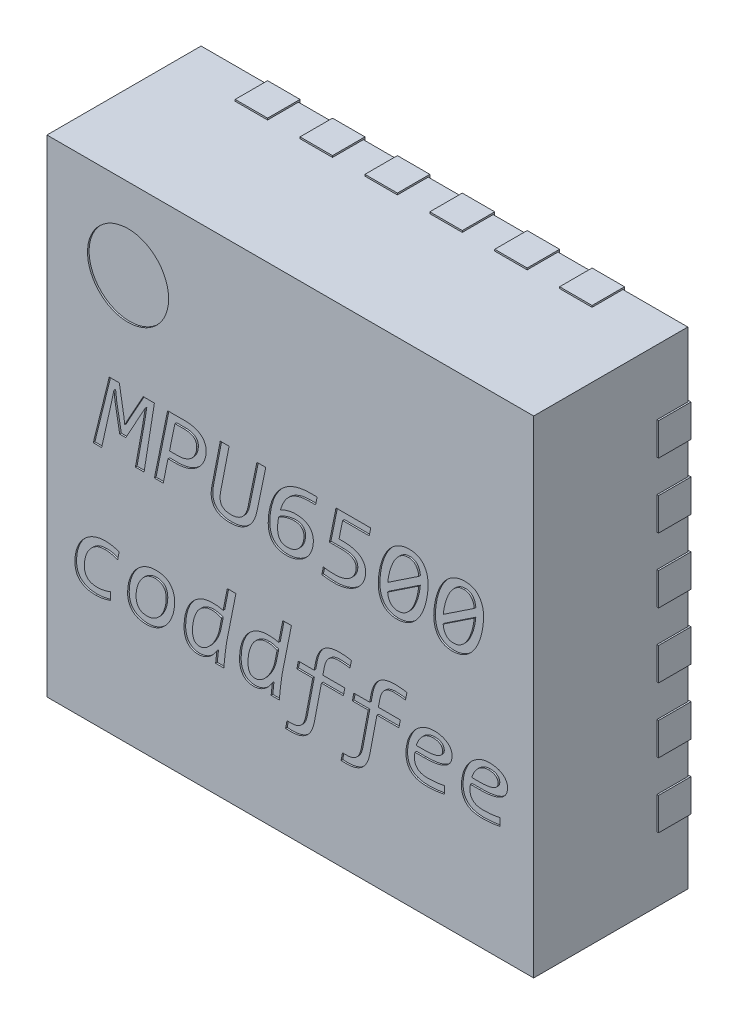
SolidWorks part; units mm, degrees
material "1023 碳钢板 (SS)"
ref_plane "前视基准面" through (0, 0, 0) normal (0, 0, 1) x (1, 0, 0)
ref_plane "上视基准面" through (0, 0, 0) normal (0, 1, 0) x (1, 0, 0)
ref_plane "右视基准面" through (0, 0, 0) normal (1, 0, 0) x (0, 0, -1)
ref_plane "芯片基底面" through (0, 0, 0.01) normal (0, 0, 1) x (1, 0, 0)
sketch "草图1" plane through (0, 0, 0.01) normal (0, 0, 1) x (1, 0, 0)
  line L1 (-1.5, 1.5) -> (1.5, 1.5)
  line L2 (-1.5, 1.5) -> (-1.5, -1.5)
  line L3 (-1.5, -1.5) -> (1.5, -1.5)
  line L4 (1.5, 1.5) -> (1.5, -1.5)
  line L5 (-1.5, 1.5) -> (1.5, -1.5) construction
  line L6 (-1.5, -1.5) -> (1.5, 1.5) construction
  point P0 (0, 0)
extrude "凸台-拉伸1" add sketch "草图1" along normal blind 0.95
sketch "草图2" plane through (0, 0, 0) normal (0, 0, 1) x (1, 0, 0)
  line L0 (0.5, 1.5) -> (0.5, 1.51)
  line L2 (0.9, 1.5) -> (0.9, 1.51)
  line L8 (1.1, 1.51) -> (1.1, 1.2)
  line L9 (1.1, 1.2) -> (0.9, 1.2)
  line L10 (0.9, 1.5) -> (0.9, 1.2)
  line L11 (0.7, 1.51) -> (0.7, 1.2)
  line L12 (0.7, 1.2) -> (0.5, 1.2)
  line L13 (0.9, 1.51) -> (1.1, 1.51)
  line L14 (0.5, 1.5) -> (0.5, 1.2)
  line L15 (0.5, 1.51) -> (0.7, 1.51)
  line L16 (0.1, 1.5) -> (0.1, 1.51)
  line L17 (0.3, 1.51) -> (0.3, 1.2)
  line L18 (0.3, 1.2) -> (0.1, 1.2)
  line L19 (0.1, 1.5) -> (0.1, 1.2)
  line L20 (0.1, 1.51) -> (0.3, 1.51)
  line L21 (-0.3, 1.5) -> (-0.3, 1.51)
  line L22 (-0.1, 1.51) -> (-0.1, 1.2)
  line L23 (-0.1, 1.2) -> (-0.3, 1.2)
  line L24 (-0.3, 1.5) -> (-0.3, 1.2)
  line L25 (-0.3, 1.51) -> (-0.1, 1.51)
  line L26 (-0.7, 1.5) -> (-0.7, 1.51)
  line L27 (-0.5, 1.51) -> (-0.5, 1.2)
  line L28 (-0.5, 1.2) -> (-0.7, 1.2)
  line L29 (-0.7, 1.5) -> (-0.7, 1.2)
  line L30 (-0.7, 1.51) -> (-0.5, 1.51)
  line L31 (-1.1, 1.5) -> (-1.1, 1.51)
  line L32 (-0.9, 1.51) -> (-0.9, 1.2)
  line L33 (-0.9, 1.2) -> (-1.1, 1.2)
  line L34 (-1.1, 1.5) -> (-1.1, 1.2)
  line L35 (-1.1, 1.51) -> (-0.9, 1.51)
  line L36 (1.5, -0.5) -> (1.51, -0.5)
  line L37 (1.5, -0.9) -> (1.51, -0.9)
  line L38 (1.51, -1.1) -> (1.2, -1.1)
  line L39 (1.2, -1.1) -> (1.2, -0.9)
  line L40 (1.5, -0.9) -> (1.2, -0.9)
  line L41 (1.51, -0.7) -> (1.2, -0.7)
  line L42 (1.2, -0.7) -> (1.2, -0.5)
  line L43 (1.51, -0.9) -> (1.51, -1.1)
  line L44 (1.5, -0.5) -> (1.2, -0.5)
  line L45 (1.51, -0.5) -> (1.51, -0.7)
  line L46 (1.5, -0.1) -> (1.51, -0.1)
  line L47 (1.51, -0.3) -> (1.2, -0.3)
  line L48 (1.2, -0.3) -> (1.2, -0.1)
  line L49 (1.5, -0.1) -> (1.2, -0.1)
  line L50 (1.51, -0.1) -> (1.51, -0.3)
  line L51 (1.5, 0.3) -> (1.51, 0.3)
  line L52 (1.51, 0.1) -> (1.2, 0.1)
  line L53 (1.2, 0.1) -> (1.2, 0.3)
  line L54 (1.5, 0.3) -> (1.2, 0.3)
  line L55 (1.51, 0.3) -> (1.51, 0.1)
  line L56 (1.5, 0.7) -> (1.51, 0.7)
  line L57 (1.51, 0.5) -> (1.2, 0.5)
  line L58 (1.2, 0.5) -> (1.2, 0.7)
  line L59 (1.5, 0.7) -> (1.2, 0.7)
  line L60 (1.51, 0.7) -> (1.51, 0.5)
  line L61 (1.5, 1.1) -> (1.51, 1.1)
  line L62 (1.51, 0.9) -> (1.2, 0.9)
  line L63 (1.2, 0.9) -> (1.2, 1.1)
  line L64 (1.5, 1.1) -> (1.2, 1.1)
  line L65 (1.51, 1.1) -> (1.51, 0.9)
  line L66 (-0.5, -1.5) -> (-0.5, -1.51)
  line L67 (-0.9, -1.5) -> (-0.9, -1.51)
  line L68 (-1.1, -1.51) -> (-1.1, -1.2)
  line L69 (-1.1, -1.2) -> (-0.9, -1.2)
  line L70 (-0.9, -1.5) -> (-0.9, -1.2)
  line L71 (-0.7, -1.51) -> (-0.7, -1.2)
  line L72 (-0.7, -1.2) -> (-0.5, -1.2)
  line L73 (-0.9, -1.51) -> (-1.1, -1.51)
  line L74 (-0.5, -1.5) -> (-0.5, -1.2)
  line L75 (-0.5, -1.51) -> (-0.7, -1.51)
  line L76 (-0.1, -1.5) -> (-0.1, -1.51)
  line L77 (-0.3, -1.51) -> (-0.3, -1.2)
  line L78 (-0.3, -1.2) -> (-0.1, -1.2)
  line L79 (-0.1, -1.5) -> (-0.1, -1.2)
  line L80 (-0.1, -1.51) -> (-0.3, -1.51)
  line L81 (0.3, -1.5) -> (0.3, -1.51)
  line L82 (0.1, -1.51) -> (0.1, -1.2)
  line L83 (0.1, -1.2) -> (0.3, -1.2)
  line L84 (0.3, -1.5) -> (0.3, -1.2)
  line L85 (0.3, -1.51) -> (0.1, -1.51)
  line L86 (0.7, -1.5) -> (0.7, -1.51)
  line L87 (0.5, -1.51) -> (0.5, -1.2)
  line L88 (0.5, -1.2) -> (0.7, -1.2)
  line L89 (0.7, -1.5) -> (0.7, -1.2)
  line L90 (0.7, -1.51) -> (0.5, -1.51)
  line L91 (1.1, -1.5) -> (1.1, -1.51)
  line L92 (0.9, -1.51) -> (0.9, -1.2)
  line L93 (0.9, -1.2) -> (1.1, -1.2)
  line L94 (1.1, -1.5) -> (1.1, -1.2)
  line L95 (1.1, -1.51) -> (0.9, -1.51)
  line L96 (-1.5, 0.5) -> (-1.51, 0.5)
  line L97 (-1.5, 0.9) -> (-1.51, 0.9)
  line L98 (-1.51, 1.1) -> (-1.2, 1.1)
  line L99 (-1.2, 1.1) -> (-1.2, 0.9)
  line L100 (-1.5, 0.9) -> (-1.2, 0.9)
  line L101 (-1.51, 0.7) -> (-1.2, 0.7)
  line L102 (-1.2, 0.7) -> (-1.2, 0.5)
  line L103 (-1.51, 0.9) -> (-1.51, 1.1)
  line L104 (-1.5, 0.5) -> (-1.2, 0.5)
  line L105 (-1.51, 0.5) -> (-1.51, 0.7)
  line L106 (-1.5, 0.1) -> (-1.51, 0.1)
  line L107 (-1.51, 0.3) -> (-1.2, 0.3)
  line L108 (-1.2, 0.3) -> (-1.2, 0.1)
  line L109 (-1.5, 0.1) -> (-1.2, 0.1)
  line L110 (-1.51, 0.1) -> (-1.51, 0.3)
  line L111 (-1.5, -0.3) -> (-1.51, -0.3)
  line L112 (-1.51, -0.1) -> (-1.2, -0.1)
  line L113 (-1.2, -0.1) -> (-1.2, -0.3)
  line L114 (-1.5, -0.3) -> (-1.2, -0.3)
  line L115 (-1.51, -0.3) -> (-1.51, -0.1)
  line L116 (-1.5, -0.7) -> (-1.51, -0.7)
  line L117 (-1.51, -0.5) -> (-1.2, -0.5)
  line L118 (-1.2, -0.5) -> (-1.2, -0.7)
  line L119 (-1.5, -0.7) -> (-1.2, -0.7)
  line L120 (-1.51, -0.7) -> (-1.51, -0.5)
  line L121 (-1.5, -1.1) -> (-1.51, -1.1)
  line L122 (-1.51, -0.9) -> (-1.2, -0.9)
  line L123 (-1.2, -0.9) -> (-1.2, -1.1)
  line L124 (-1.5, -1.1) -> (-1.2, -1.1)
  line L125 (-1.51, -1.1) -> (-1.51, -0.9)
  point P123 (0, 0)
  dimension "D1" = 6
  dimension "D2" = 4
extrude "凸台-拉伸2" add sketch "草图2" along normal blind 0.2
sketch "草图3" plane through (0, 0, 0) normal (0, 0, 1) x (1, 0, 0)
  line L0 (-0.6, 0.77) -> (-0.85, 0.52)
  line L1 (0.75, 0.77) -> (-0.6, 0.77)
  line L2 (0.85, 0.67) -> (0.85, -0.67)
  line L3 (0.75, -0.77) -> (-0.75, -0.77)
  line L4 (-0.85, 0.52) -> (-0.85, -0.67)
  arc A0 (-0.85, -0.67) -> (-0.75, -0.77) centre (-0.75, -0.67) ccw
  arc A1 (0.75, -0.77) -> (0.85, -0.67) centre (0.75, -0.67) ccw
  arc A2 (0.85, 0.67) -> (0.75, 0.77) centre (0.75, 0.67) ccw
  point P0 (0, 0)
  point P4 (-0.85, 0.77)
  dimension "D1" = 0.1
extrude "凸台-拉伸3" add sketch "草图3" along normal blind 0.01
sketch "草图4" plane through (0, 0, 0.96) normal (0, 0, 1) x (1, 0, 0)
  line L0 (-1.5, 0) -> (1.5, 0) construction
  line L2 (-1.5, 1.5) -> (-1.5, -1.5) construction
  line L3 (1.5, -1.5) -> (1.5, 1.5) construction
  line L5 (-1.5, -0.8) -> (1.5, -0.8) construction
  circle A0 centre (-1, 1) radius 0.25
  text T0 "<i>MPU6500</i>" font "Consolas" height 0.4
  text T1 "<i>coddffee</i>" font "Consolas" height 0.4
extrude "切除-拉伸1" cut sketch "草图4" against normal blind 0.01
